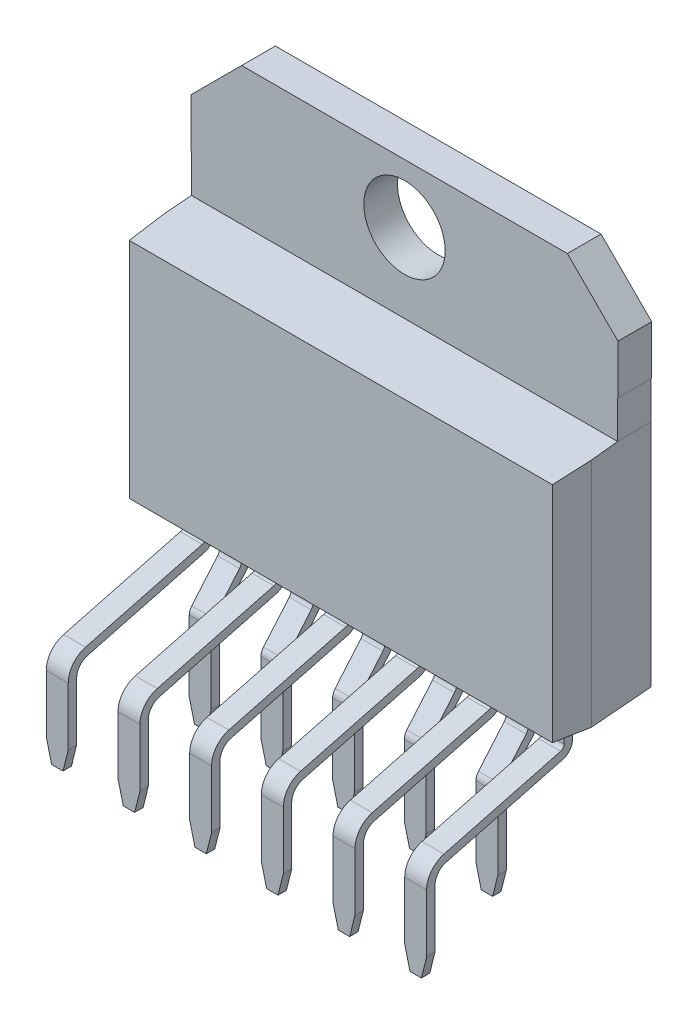
SolidWorks part; units mm, degrees
ref_plane "Спереди" through (0, 0, 0) normal (0, 0, 1) x (1, 0, 0)
ref_plane "Сверху" through (0, 0, 0) normal (0, 1, 0) x (1, 0, 0)
ref_plane "Справа" through (0, 0, 0) normal (1, 0, 0) x (0, 0, -1)
sketch "Эскиз1" plane through (0, 0, 0) normal (1, 0, 0) x (0, 0, -1)
  line L0 (-4.62, 5.3) -> (-4.62, -5.3)
  line L1 (0, -5.3) -> (-2.85, -5.5)
  line L2 (0, 5.6) -> (0, -5.3)
  line L3 (0, 5.6) -> (-1.6, 5.6)
  line L4 (-1.6, 5.6) -> (-4.62, 5.3)
  line L5 (-10.8227, 0) -> (10.3095, 0) construction
  line L6 (-2.85, -5.5) -> (-4.62, -5.3)
  dimension "D1" = 11.1
  dimension "D2" = 4.62
  dimension "D3" = 1.6
  dimension "D4" = 0.3
  dimension "D5" = 0.2
  dimension "D6" = 0.2
  dimension "D7" = 2.85
extrude "Бобышка-Вытянуть1" add sketch "Эскиз1" along normal mid plane 20.27
sketch "Эскиз2" plane through (0, 5.6, 0) normal (0, 1, 0) x (1, 0, 0)
  line L0 (-10.135, 0) -> (-10.135, -4.62)
  line L1 (-10.135, -4.62) -> (-10.035, -4.62)
  line L3 (10.135, -4.62) -> (-10.135, -4.62) construction
  line L4 (-10.035, -4.62) -> (-10.125, -2.85)
  line L6 (-10.125, -2.85) -> (-10.085, 0)
  line L7 (0, 1.8865) -> (0, -5.9946) construction
  line L8 (10.135, 0) -> (-10.135, 0) construction
  line L9 (-10.085, 0) -> (-10.135, 0)
  line L10 (10.085, 0) -> (10.135, 0)
  line L11 (10.125, -2.85) -> (10.085, 0)
  line L12 (10.035, -4.62) -> (10.125, -2.85)
  line L13 (10.135, -4.62) -> (10.035, -4.62)
  line L14 (10.135, 0) -> (10.135, -4.62)
  dimension "D1" = 0.01
  dimension "D2" = 0.1
  dimension "D3" = 2.85
  dimension "D4" = 0.05
extrude "Вырез-Вытянуть1" cut sketch "Эскиз2" against normal blind 11.1
sketch "Эскиз3" plane through (0, 0, 0) normal (0, 0, 1) x (1, 0, 0)
  line L0 (-10.125, 9.73) -> (-10.125, 5.6)
  line L1 (-10.125, 5.6) -> (10.125, 5.6)
  line L2 (10.125, 9.73) -> (7.725, 12.13)
  line L3 (7.725, 12.13) -> (-7.725, 12.13)
  line L4 (-7.725, 12.13) -> (-10.125, 9.73)
  line L5 (10.125, 5.6) -> (10.125, 9.73)
  line L6 (0, 16.4744) -> (0, -7.0617) construction
  line L7 (10.125, -5.5) -> (-10.125, -5.5) construction
  circle A0 centre (0, 9.34) radius 1.93
  dimension "D2" = 3.86
  dimension "D1" = 2.79
  dimension "D3" = 17.63
  dimension "D4" = 2.4
  dimension "D5" = 2.4
  dimension "D6" = 2.4
  dimension "D7" = 6.53
  dimension "D8" = 20.25
extrude "Бобышка-Вытянуть2" add sketch "Эскиз3" along normal blind 1.6 separate body
sketch "Эскиз4" plane through (0, 5.6, 0) normal (0, -1, 0) x (1, 0, 0)
  line L0 (-10.1075, 1.6) -> (-10.085, 0)
  line L1 (-10.1075, 1.6) -> (-10.125, 1.6)
  line L2 (-10.125, 1.6) -> (-10.125, 0)
  line L3 (-10.125, 0) -> (-10.085, 0)
  line L4 (0, 6.0625) -> (0, -1.2471) construction
  line L5 (10.125, 0) -> (10.085, 0)
  line L7 (10.125, 1.6) -> (10.125, 0)
  line L8 (10.1075, 1.6) -> (10.125, 1.6)
  line L9 (10.1075, 1.6) -> (10.085, 0)
extrude "Вырез-Вытянуть2" cut sketch "Эскиз4" against normal blind 1.8
sketch "Эскиз5" plane through (0, 0, 0) normal (1, 0, 0) x (0, 0, -1)
  line L0 (-6.8445, 0) -> (2.0976, 0) construction
  line L1 (-2.85, -6.7773) -> (-2.85, 0)
  line L3 (-2.9932, -7.1663) -> (-4.2184, -8.605)
  line L4 (-4.29, -8.7996) -> (-4.29, -13.16)
  line L5 (0, -5.3) -> (0, 5.6) construction
  line L6 (-2.85, -5.5) -> (-2.85, 5.4758) construction
  arc A0 (-2.85, -6.7773) -> (-2.9932, -7.1663) centre (-3.45, -6.7773) cw
  arc A1 (-4.29, -8.7996) -> (-4.2184, -8.605) centre (-3.99, -8.7996) cw
  dimension "D4" = 0.3
  dimension "D5" = 0.6
  dimension "D1" = 13.16
  dimension "D2" = 6.7773
  dimension "D3" = 4.29
  dimension "D6" = 4.3604
  dimension "D7" = 2.85
sketch "Эскиз6" plane through (0, 0, 0) normal (0, 1, 0) x (1, 0, 0)
  line L0 (-0.52, -2.65) -> (-0.52, -3.05)
  line L1 (-0.52, -3.05) -> (0.52, -3.05)
  line L2 (0.52, -3.05) -> (0.52, -2.65)
  line L3 (-0.52, -2.65) -> (0.52, -2.65)
  line L4 (0, -2.9932) -> (0, -4.2184) construction
  line L7 (7.725, 0) -> (-7.725, 0) construction
  dimension "D1" = 1.04
  dimension "D2" = 0.4
  dimension "D3" = 0.52
  dimension "D4" = 2.65
sweep "По траектории2" add profiles "Эскиз6" path "Эскиз5"
pattern_linear "Линейный массив1" count 3 spacing 3.4 along (-1, 0, 0) count 3 spacing 3.4 along (1, 0, 0) of "По траектории2"
ref_plane "Плоскость2" through (-8.5, 0, 0) normal (1, 0, 0) x (0, 0, -1)
sketch "Эскиз7" plane through (-8.5, 0, 0) normal (1, 0, 0) x (0, 0, -1)
  line L0 (-9.37, -13.1222) -> (-9.37, -9.3822)
  line L1 (-11.0218, 0) -> (6.6147, 0) construction
  line L2 (-2.85, 0) -> (-2.85, -6.6518)
  line L3 (-2.85, -5.5) -> (-2.85, 5.4758) construction
  line L4 (-3.1616, -7.0559) -> (-8.6989, -8.5118)
  line L5 (0, -5.3) -> (0, 5.6) construction
  arc A0 (-8.6989, -8.5118) -> (-9.37, -9.3822) centre (-8.47, -9.3822) ccw
  arc A1 (-2.85, -6.6518) -> (-3.1616, -7.0559) centre (-3.2678, -6.6518) cw
  dimension "D1" = 0.9
  dimension "D3" = 0.4178
  dimension "D2" = 9.37
  dimension "D4" = 13.1222
  dimension "D5" = 3.74
  dimension "D6" = 6.6518
sketch "Эскиз8" plane through (0, 0, 0) normal (0, 1, 0) x (1, 0, 0)
  line L0 (-9.02, -2.65) -> (-7.98, -2.65)
  line L1 (-7.98, -2.65) -> (-7.98, -3.05)
  line L2 (-7.98, -3.05) -> (-9.02, -3.05)
  line L3 (-9.02, -3.05) -> (-9.02, -2.65)
  line L4 (10.125, 0) -> (7.725, 0) construction
  line L5 (-8.5, -3.1616) -> (-8.5, -8.6989) construction
  dimension "D1" = 1.04
  dimension "D2" = 0.4
  dimension "D3" = 2.65
  dimension "D4" = 0.52
sweep "По траектории3" add profiles "Эскиз8" path "Эскиз7"
pattern_linear "Линейный массив2" count 6 spacing 3.4 along (1, 0, 0) of "По траектории3"
chamfer "Фаска1" distance 0.25 distance2 1 22 edges at (4.58, -13.1222, 9.37) (5.62, -13.1222, 9.37) (2.22, -13.1222, 9.37) (1.18, -13.1222, 9.37) (-1.18, -13.1222, 9.37) (-2.22, -13.1222, 9.37) (-5.62, -13.1222, 9.37) (-4.58, -13.1222, 9.37) (-9.02, -13.1222, 9.37) (-7.98, -13.1222, 9.37) (7.98, -13.1222, 9.37) (9.02, -13.1222, 9.37) (7.32, -13.16, 4.29) (6.28, -13.16, 4.29) (3.92, -13.16, 4.29) (2.88, -13.16, 4.29) (-2.88, -13.16, 4.29) (-3.92, -13.16, 4.29) (-6.28, -13.16, 4.29) (-7.32, -13.16, 4.29) (0.52, -13.16, 4.29) (-0.52, -13.16, 4.29)
sketch "Эскиз10" plane through (0, 0, 4.62) normal (0, 0, 1) x (1, 0, 0)
  text T0 "TO-220-11" font "Arial" height in points 10
extrude "Вырез-Вытянуть3" [suppressed] cut sketch "Эскиз10" against normal blind 0.1
